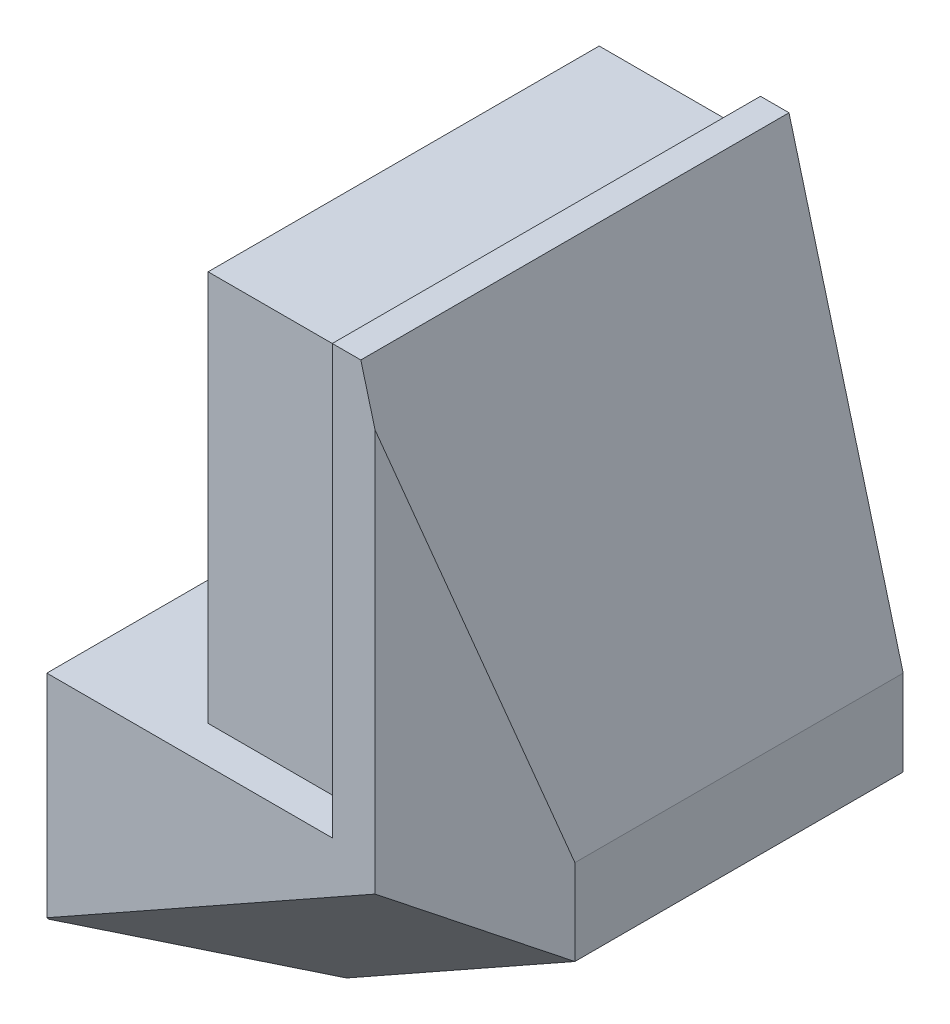
SolidWorks part; units mm, degrees
ref_plane "Plano frontal" through (0, 0, 0) normal (0, 0, 1) x (1, 0, 0)
ref_plane "Plano superior" through (0, 0, 0) normal (0, 1, 0) x (1, 0, 0)
ref_plane "Plano direito" through (0, 0, 0) normal (1, 0, 0) x (0, 0, -1)
sketch "Esboço1" plane through (0, 0, 0) normal (0, 0, 1) x (1, 0, 0)
  line L0 (0, 0) -> (0, 30)
  line L1 (0, 30) -> (2, 30)
  line L2 (2, 30) -> (10, 0)
  line L3 (10, 0) -> (10, -6)
  line L4 (10, -6) -> (-6, -15)
  line L5 (-6, -15) -> (-20, -15)
  line L6 (-20, -15) -> (-20, 0)
  line L7 (-20, 0) -> (0, 0)
  dimension "D1" = 30
  dimension "D2" = 2
  dimension "D3" = 10
  dimension "D4" = 6
  dimension "D5" = 15
  dimension "D6" = 20
  dimension "D7" = 14
extrude "Ressalto-extrusão1" add sketch "Esboço1" along normal blind 30
sketch "Esboço2" plane through (0, -15, 0) normal (0, -1, 0) x (1, 0, 0)
  line L0 (-20, 30) -> (-20, 0) construction
  line L1 (-20, 30) -> (-6, 30) construction
  circle A0 centre (-12.5, 15) radius 5
  dimension "D2" = 10
  dimension "D1" = 7.5
  dimension "D3" = 15
extrude "Corte-extrusão1" cut sketch "Esboço2" against normal blind 6
chamfer "Chanfro1" distance 7 angle 45 2 edges at (2, -10.5, 30) (10, -3, 30)
sketch "Esboço3" plane through (0, -9, 0) normal (0, -1, 0) x (1, 0, 0)
  circle A0 centre (-12.5, 15) radius 2.75
  dimension "D1" = 5.5
extrude "Corte-extrusão2" cut sketch "Esboço3" against normal through all
sketch "Esboço4" plane through (0, 0, 0) normal (-1, 0, 0) x (0, 0, 1)
  line L8 (1.3, 28.7) -> (1.3, 1.3)
  line L9 (1.3, 1.3) -> (28.7, 1.3)
  line L10 (28.7, 1.3) -> (28.7, 28.7)
  line L11 (28.7, 28.7) -> (1.3, 28.7)
  line L12 (1.3, 28.7) -> (1.3, 1.3)
  line L13 (1.3, 1.3) -> (28.7, 1.3)
  line L14 (28.7, 1.3) -> (28.7, 28.7)
  line L15 (28.7, 28.7) -> (1.3, 28.7)
  dimension "D1" = 1.3
extrude "Ressalto-extrusão2" add sketch "Esboço4" along normal blind 10
sketch "Esboço5" plane through (-10, 0, 0) normal (-1, 0, 0) x (0, 0, 1)
  line L8 (27.4, 27.4) -> (2.6, 27.4)
  line L9 (2.6, 27.4) -> (2.6, 2.6)
  line L10 (2.6, 2.6) -> (27.4, 2.6)
  line L11 (27.4, 2.6) -> (27.4, 27.4)
  line L12 (27.4, 27.4) -> (2.6, 27.4)
  line L13 (2.6, 27.4) -> (2.6, 2.6)
  line L14 (2.6, 2.6) -> (27.4, 2.6)
  line L15 (27.4, 2.6) -> (27.4, 27.4)
  dimension "D1" = 1.3
extrude "Corte-extrusão3" cut sketch "Esboço5" against normal blind 12 draft 40
